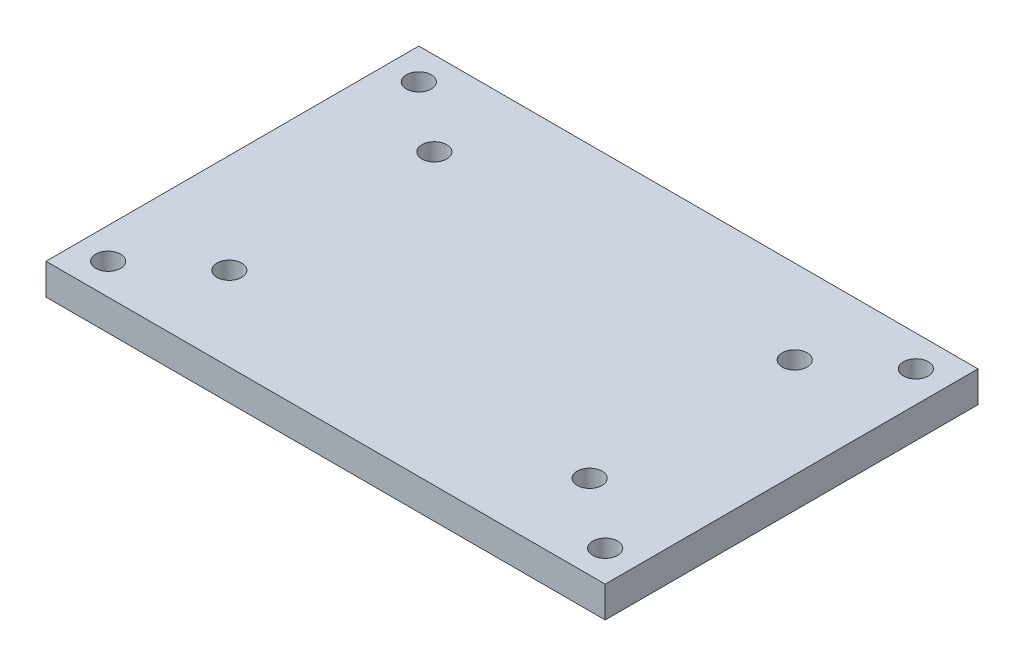
SolidWorks part; units mm, degrees
ref_plane "Front Plane" through (0, 0, 0) normal (0, 0, 1) x (1, 0, 0)
ref_plane "Top Plane" through (0, 0, 0) normal (0, 1, 0) x (1, 0, 0)
ref_plane "Right Plane" through (0, 0, 0) normal (1, 0, 0) x (0, 0, -1)
sketch "草图1" plane through (0, 0, 0) normal (0, 1, 0) x (1, 0, 0)
  line L0 (0, 41.682) -> (0, -51.3594) construction
  line L1 (-74.3553, 0) -> (56.165, 0) construction
  line L2 (45, -30) -> (-45, -30)
  line L3 (45, -30) -> (45, 30)
  line L4 (45, 30) -> (-45, 30)
  line L5 (-45, -30) -> (-45, 30)
  line L6 (45, -30) -> (-45, 30) construction
  line L7 (45, 30) -> (-45, -30) construction
  circle A0 centre (-40, 25) radius 2
  circle A1 centre (40, 25) radius 2
  circle A2 centre (40, -25) radius 2
  circle A3 centre (-40, -25) radius 2
  circle A4 centre (-29, 16.5) radius 2
  circle A5 centre (29, 16.5) radius 2
  circle A6 centre (29, -16.5) radius 2
  circle A7 centre (-29, -16.5) radius 2
  point P2 (0, 0)
  dimension "D5" = 4
  dimension "D6" = 4
  dimension "D9" = 4
  dimension "D1" = 90
  dimension "D2" = 60
  dimension "D3" = 80
  dimension "D4" = 40
  dimension "D7" = 5
  dimension "D8" = 5
  dimension "D10" = 29
  dimension "D11" = 16.5
extrude "凸台-拉伸1" add sketch "草图1" along normal blind 5
